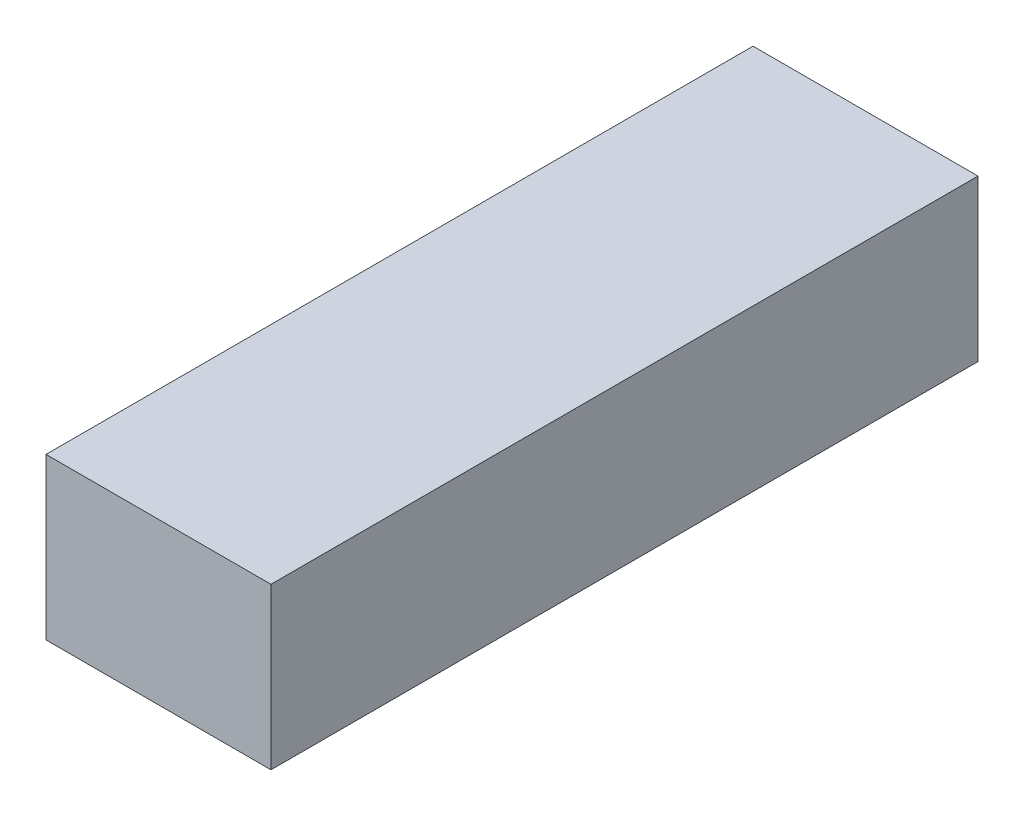
SolidWorks part; units mm, degrees
ref_plane "Front Plane" through (0, 0, 0) normal (0, 0, 1) x (1, 0, 0)
ref_plane "Top Plane" through (0, 0, 0) normal (0, 1, 0) x (1, 0, 0)
ref_plane "Right Plane" through (0, 0, 0) normal (1, 0, 0) x (0, 0, -1)
sketch "Sketch1" plane through (0, 0, 0) normal (0, 1, 0) x (1, 0, 0)
  line L1 (-22.225, 69.85) -> (22.225, 69.85)
  line L2 (-22.225, 69.85) -> (-22.225, -69.85)
  line L3 (-22.225, -69.85) -> (22.225, -69.85)
  line L4 (22.225, 69.85) -> (22.225, -69.85)
  point P4 (0, 69.85)
  point P6 (-22.225, 0)
  dimension "D1" = 44.45
  dimension "D2" = 139.7
extrude "Boss-Extrude1" add sketch "Sketch1" along normal blind 31.75
